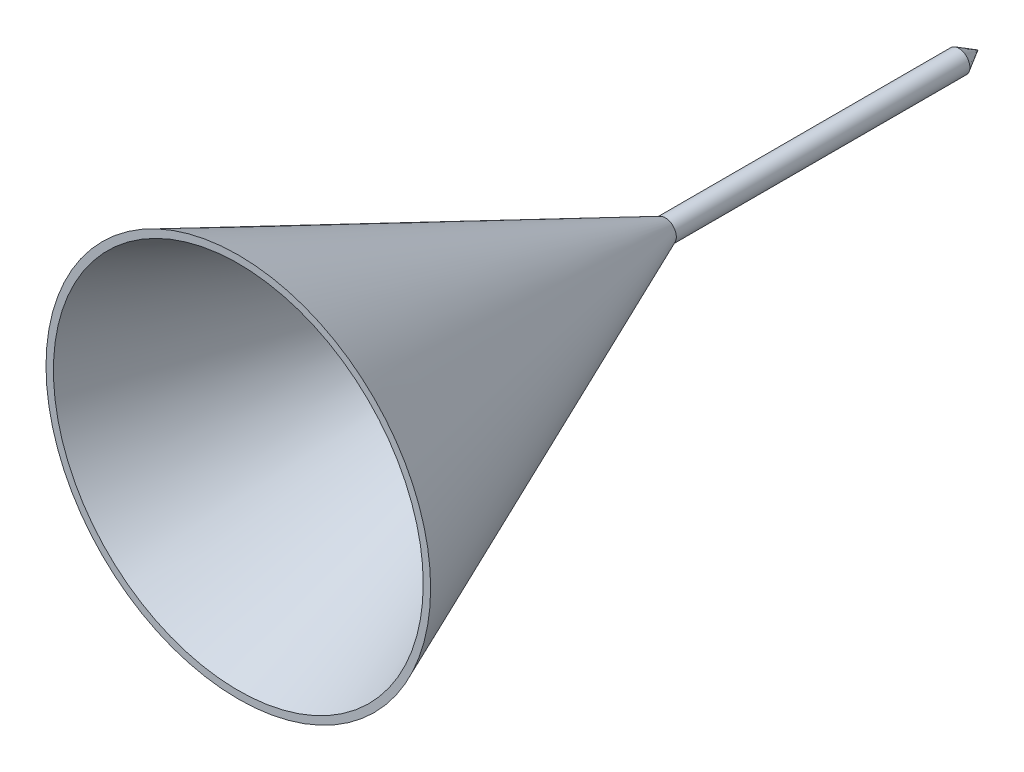
SolidWorks part; units mm, degrees
material "6061-T6 (SS)"
ref_plane "Front Plane" through (0, 0, 0) normal (0, 0, 1) x (1, 0, 0)
ref_plane "Top Plane" through (0, 0, 0) normal (0, 1, 0) x (1, 0, 0)
ref_plane "Right Plane" through (0, 0, 0) normal (1, 0, 0) x (0, 0, -1)
sketch "Sketch2" plane through (0, 0, 0) normal (0, 1, 0) x (1, 0, 0)
  line L0 (3810, 0) -> (3962.4, 0)
  line L1 (3810, 0) -> (76.2, 8796.2816)
  line L2 (76.2, 8796.2816) -> (76.2, 14879.4177)
  line L3 (76.2, 14879.4177) -> (0, 15011.4)
  line L4 (0, 0) -> (0, 16877.9613) construction
  line L5 (0, 15011.4) -> (0, 15240)
  line L6 (0, 15240) -> (228.6, 14844.0532)
  line L7 (228.6, 14844.0532) -> (228.6, 8796.2816)
  line L8 (228.6, 8796.2816) -> (3962.4, 0)
  line L9 (228.6, 8796.2816) -> (76.2, 8796.2816) construction
  dimension "D1" = 152.4
  dimension "D2" = 3810
  dimension "D3" = 152.4
  dimension "D4" = 150
  dimension "D5" = 67
  dimension "D6" = 228.6
  dimension "D7" = 15240
revolve "Revolve1" add sketch "Sketch2" angle 360 about L4
